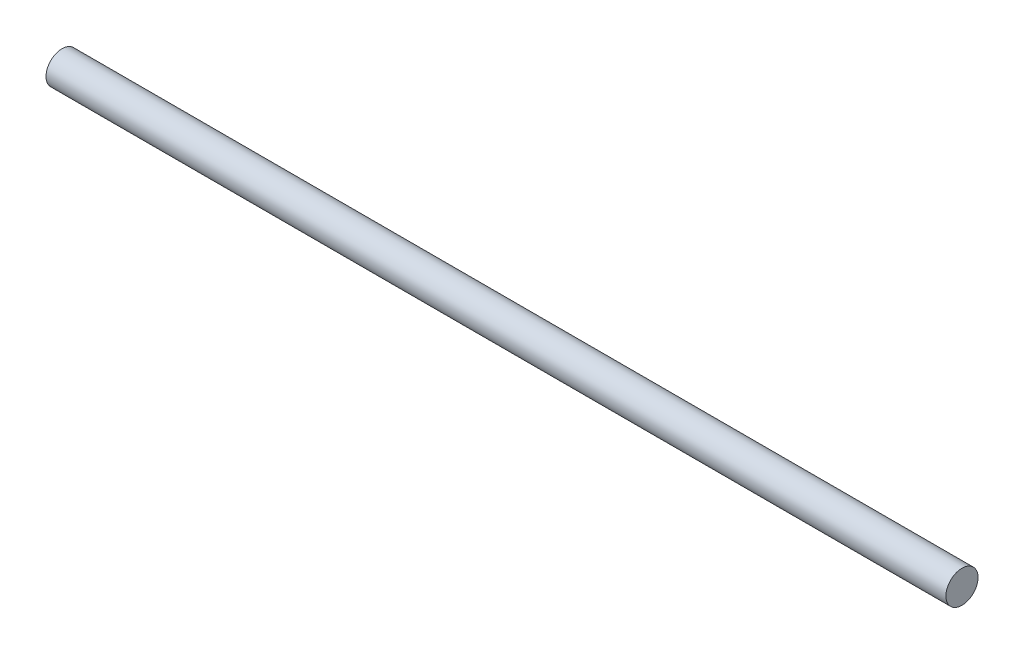
SolidWorks part; units mm, degrees
ref_plane "Plan de face" through (0, 0, 0) normal (0, 0, 1) x (1, 0, 0)
ref_plane "Plan de dessus" through (0, 0, 0) normal (0, 1, 0) x (1, 0, 0)
ref_plane "Plan de droite" through (0, 0, 0) normal (1, 0, 0) x (0, 0, -1)
sketch "Esquisse1" plane through (0, 0, 0) normal (0, 0, 1) x (1, 0, 0)
  line L1 (-112, -2) -> (112, -2)
  line L2 (-112, -2) -> (-112, 2)
  line L3 (-112, 2) -> (112, 2)
  line L4 (112, -2) -> (112, 2)
  line L5 (-112, -2) -> (112, 2) construction
  line L6 (-112, 2) -> (112, -2) construction
  point P0 (0, 0)
  dimension "D1" = 224
  dimension "D2" = 4
revolve "Révolution1" add sketch "Esquisse1" angle 360 about L1
